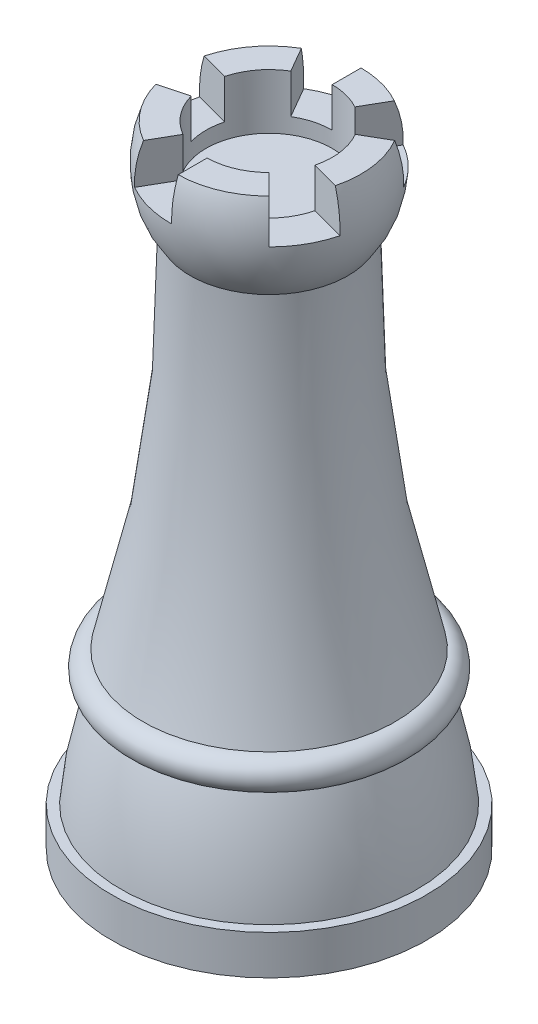
SolidWorks part; units mm, degrees
ref_plane "Front Plane" through (0, 0, 0) normal (0, 0, 1) x (1, 0, 0)
ref_plane "Top Plane" through (0, 0, 0) normal (0, 1, 0) x (1, 0, 0)
ref_plane "Right Plane" through (0, 0, 0) normal (1, 0, 0) x (0, 0, -1)
sketch "Sketch1" plane through (0, 0, 0) normal (0, 0, 1) x (1, 0, 0)
  line L0 (0, 0) -> (12.7, 0)
  line L1 (12.7, 0) -> (12.7, 3.175)
  line L2 (12.7, 3.175) -> (11.938, 3.175)
  line L3 (0, 0) -> (0, 50.8)
  line L4 (0, 50.8) -> (7.4053, 50.8)
  arc A2 (10.16, 13.97) -> (10.16, 11.43) centre (10.16, 12.7) cw
  arc A4 (10.16, 11.43) -> (11.938, 3.175) centre (-19.7136, 0.6767) cw
  arc A5 (7.4053, 50.8) -> (6.35, 43.18) centre (0, 47.9425) cw
  arc A6 (6.35, 43.18) -> (10.16, 13.97) centre (105.3911, 41.2449) ccw
  dimension "D4" = 1.27
  dimension "D6" = 6.35
  dimension "D12" = 31.75
  dimension "D7" = 7.9375
  dimension "D13" = 99.06
  dimension "D14" = 7.62
  dimension "D1" = 12.7
  dimension "D2" = 3.175
  dimension "D3" = 0.762
  dimension "D5" = 12.7
  dimension "D8" = 50.8
  dimension "D9" = 10.16
  dimension "D10" = 10.16
  dimension "D11" = 2.54
revolve "Revolve1" add sketch "Sketch1" angle 360 about L3
sketch "Sketch2" plane through (0, 50.8, 0) normal (0, 1, 0) x (1, 0, 0)
  circle A0 centre (0, 0) radius 5.08
  dimension "D1" = 10.16
extrude "Cut-Extrude1" cut sketch "Sketch2" against normal blind 4.445
sketch "Sketch3" plane through (0, 50.8, 0) normal (0, 1, 0) x (1, 0, 0)
  line L0 (0, 10.16) -> (0, 5.08)
  line L3 (-5.07, 8.6157) -> (-2.6115, 4.3573)
  circle A1 centre (0, 0) radius 5.08 construction
  arc A2 (0, 10.16) -> (-5.07, 8.6157) centre (0.3229, 0.0051) ccw
  arc A3 (0, 5.08) -> (-2.6115, 4.3573) centre (0, 0) ccw
  circle A4 centre (0, 0) radius 5.08 construction
  point P8 (0, 0)
  point P14 (-2.5132, 4.3813)
  dimension "D1" = 10.16
  dimension "D2" = 5.08
  dimension "D3" = 30
  dimension "D4" = 10.16
  dimension "D5" = 6.1811
  dimension "D6" = 6.3632
extrude "Cut-Extrude2" cut sketch "Sketch3" against normal blind 3.175
pattern_circular "CirPattern1" count 5 every 75 about axis through (0, 0, 0) along (0, 1, 0) of "Cut-Extrude2"
